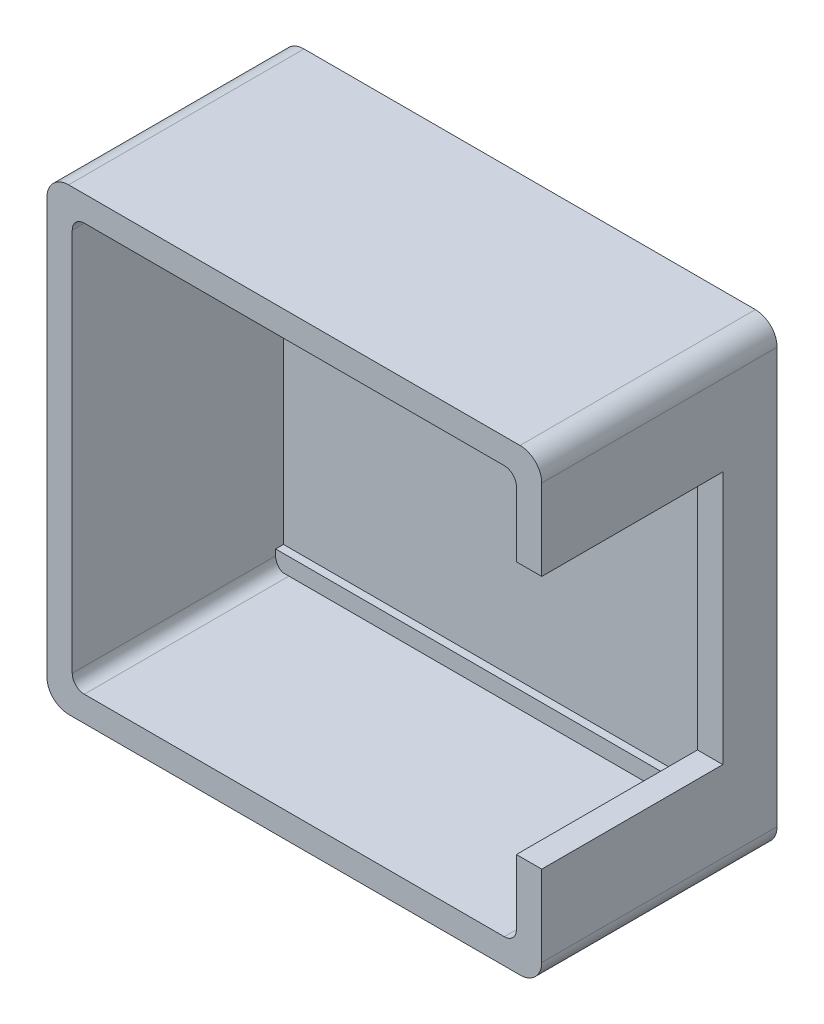
SolidWorks part; units mm, degrees
ref_plane "前视基准面" through (0, 0, 0) normal (0, 0, 1) x (1, 0, 0)
ref_plane "上视基准面" through (0, 0, 0) normal (0, 1, 0) x (1, 0, 0)
ref_plane "右视基准面" through (0, 0, 0) normal (1, 0, 0) x (0, 0, -1)
other "Configuration Table"
sketch "Factory_ABS_floor_41x38_Sketch" plane through (0, 0, 0) normal (0, 0, 1) x (1, 0, 0)
  line L0 (-18.7, -19) -> (18.7, -19)
  line L1 (20.5, -17.2) -> (20.5, 17.2)
  line L2 (18.7, 19) -> (-18.7, 19)
  line L3 (-20.5, 17.2) -> (-20.5, -17.2)
  arc A0 (18.7, -19) -> (20.5, -17.2) centre (18.7, -17.2) ccw
  arc A1 (20.5, 17.2) -> (18.7, 19) centre (18.7, 17.2) ccw
  arc A2 (-18.7, 19) -> (-20.5, 17.2) centre (-18.7, 17.2) ccw
  arc A3 (-20.5, -17.2) -> (-18.7, -19) centre (-18.7, -17.2) ccw
extrude "Factory_ABS_floor_41x38" add sketch "Factory_ABS_floor_41x38_Sketch" along normal blind 2 separate body
sketch "Factory_ABS_sidewalls_Sketch" plane through (0, 0, 0) normal (0, 0, 1) x (1, 0, 0)
  line L0 (-18.7, -19) -> (18.7, -19)
  line L1 (20.5, -17.2) -> (20.5, 17.2)
  line L2 (18.7, 19) -> (-18.7, 19)
  line L3 (-20.5, 17.2) -> (-20.5, -17.2)
  line L4 (-17.4, -16.9) -> (17.4, -16.9)
  line L5 (18.4, -15.9) -> (18.4, 15.9)
  line L6 (17.4, 16.9) -> (-17.4, 16.9)
  line L7 (-18.4, 15.9) -> (-18.4, -15.9)
  arc A0 (18.7, -19) -> (20.5, -17.2) centre (18.7, -17.2) ccw
  arc A1 (20.5, 17.2) -> (18.7, 19) centre (18.7, 17.2) ccw
  arc A2 (-18.7, 19) -> (-20.5, 17.2) centre (-18.7, 17.2) ccw
  arc A3 (-20.5, -17.2) -> (-18.7, -19) centre (-18.7, -17.2) ccw
  arc A4 (17.4, -16.9) -> (18.4, -15.9) centre (17.4, -15.9) ccw
  arc A5 (18.4, 15.9) -> (17.4, 16.9) centre (17.4, 15.9) ccw
  arc A6 (-17.4, 16.9) -> (-18.4, 15.9) centre (-17.4, 15.9) ccw
  arc A7 (-18.4, -15.9) -> (-17.4, -16.9) centre (-17.4, -15.9) ccw
extrude "Factory_ABS_sidewalls" add sketch "Factory_ABS_sidewalls_Sketch" along normal blind 17.5 from offset 2
sketch "Factory_terminal_opening_Sketch" plane through (0, 0, 0) normal (0, 0, 1) x (1, 0, 0)
  line L0 (18.2, -10.5) -> (21.4, -10.5)
  line L1 (21.4, -10.5) -> (21.4, 10.5)
  line L2 (21.4, 10.5) -> (18.2, 10.5)
  line L3 (18.2, 10.5) -> (18.2, -10.5)
extrude "Factory_terminal_opening" cut sketch "Factory_terminal_opening_Sketch" along normal blind 15 from offset 4.5
sketch "Factory_mounting_ear_Sketch" plane through (0, 0, 0) normal (0, 0, 1) x (1, 0, 0)
  line L0 (-23, -5) -> (-21.7, -5)
  line L1 (-19.4, -2.7) -> (-19.4, 2.7)
  line L2 (-21.7, 5) -> (-23, 5)
  line L3 (-25.3, 2.7) -> (-25.3, -2.7)
  arc A0 (-21.7, -5) -> (-19.4, -2.7) centre (-21.7, -2.7) ccw
  arc A1 (-19.4, 2.7) -> (-21.7, 5) centre (-21.7, 2.7) ccw
  arc A2 (-23, 5) -> (-25.3, 2.7) centre (-23, 2.7) ccw
  arc A3 (-25.3, -2.7) -> (-23, -5) centre (-23, -2.7) ccw
extrude "Factory_mounting_ear" add sketch "Factory_mounting_ear_Sketch" along normal blind 2
sketch "Factory_ear_reference_hole_Sketch" plane through (0, 0, 0) normal (0, 0, 1) x (1, 0, 0)
  circle A0 centre (-22.5, 0) radius 1.5
extrude "Factory_ear_reference_hole" cut sketch "Factory_ear_reference_hole_Sketch" along normal blind 2
sketch "PCB_support_ledges_Sketch" plane through (0, 0, 0) normal (0, 0, 1) x (1, 0, 0)
  line L0 (-18.45, -16.8) -> (18.45, -16.8)
  line L1 (18.45, -16.8) -> (18.45, -15.4)
  line L2 (18.45, -15.4) -> (-18.45, -15.4)
  line L3 (-18.45, -15.4) -> (-18.45, -16.8)
  line L4 (-18.45, 15.4) -> (18.45, 15.4)
  line L5 (18.45, 15.4) -> (18.45, 16.8)
  line L6 (18.45, 16.8) -> (-18.45, 16.8)
  line L7 (-18.45, 16.8) -> (-18.45, 15.4)
extrude "PCB_support_ledges" add sketch "PCB_support_ledges_Sketch" along normal blind 0.65 from offset 2
